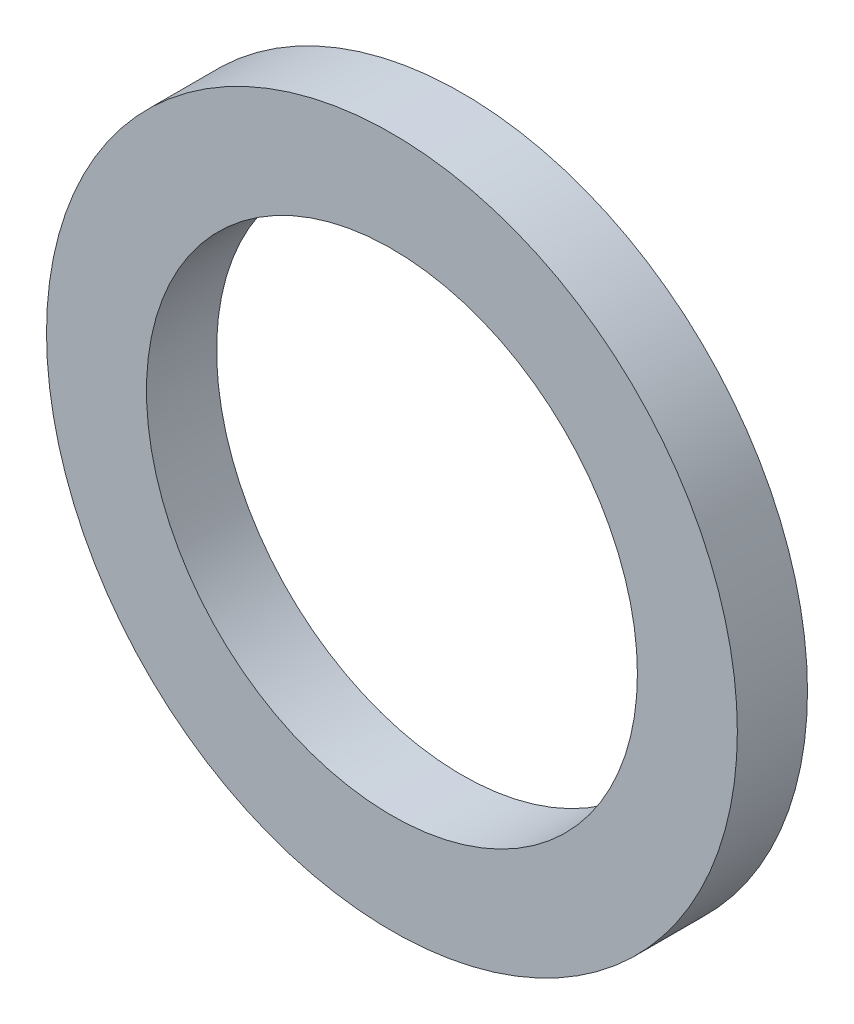
SolidWorks part; units mm, degrees
material "PET"
ref_plane "Front Plane" through (0, 0, 0) normal (0, 0, 1) x (1, 0, 0)
ref_plane "Top Plane" through (0, 0, 0) normal (0, 1, 0) x (1, 0, 0)
ref_plane "Right Plane" through (0, 0, 0) normal (1, 0, 0) x (0, 0, -1)
sketch "Sketch1" plane through (0, 0, 0) normal (0, 0, 1) x (1, 0, 0)
  circle A0 centre (0, 0) radius 3.5
  circle A1 centre (0, 0) radius 4.925
  dimension "D1" = 7
  dimension "D2" = 9.85
extrude "Boss-Extrude1" add sketch "Sketch1" along normal blind 1
